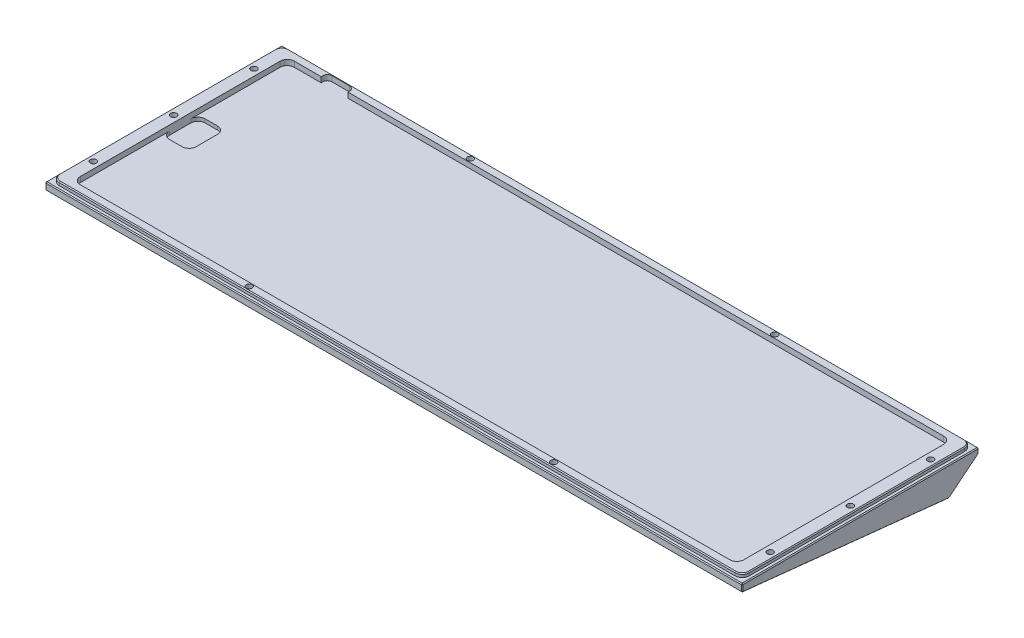
SolidWorks part; units mm, degrees
material "6061-T6 (SS)"
ref_plane "Front Plane" through (0, 0, 0) normal (0, 0, 1) x (1, 0, 0)
ref_plane "Top Plane" through (0, 0, 0) normal (0, 1, 0) x (1, 0, 0)
ref_plane "Right Plane" through (0, 0, 0) normal (1, 0, 0) x (0, 0, -1)
sketch "Sketch1" plane through (0, 0, 0) normal (0, 1, 0) x (1, 0, 0)
  line L1 (0, 0) -> (390.7, 0)
  line L2 (0, 0) -> (0, 132.7)
  line L3 (0, 132.7) -> (390.7, 132.7)
  line L4 (390.7, 0) -> (390.7, 132.7)
  dimension "D1" = 390.7
  dimension "D2" = 132.7
extrude "MainBody" add sketch "Sketch1" along normal blind 18.5
sketch "Sketch2" plane through (0, 18.5, 0) normal (0, 1, 0) x (1, 0, 0)
  line L0 (390.7, 132.7) -> (0, 132.7) construction
  line L1 (2, 130.7) -> (388.7, 130.7)
  line L2 (2, 130.7) -> (2, 2)
  line L3 (2, 2) -> (388.7, 2)
  line L4 (388.7, 130.7) -> (388.7, 2)
  line L5 (0, 132.7) -> (0, 0) construction
  line L7 (0, 132.7) -> (390.7, 132.7)
  line L8 (0, 132.7) -> (0, 0)
  line L9 (0, 0) -> (390.7, 0)
  line L10 (390.7, 132.7) -> (390.7, 0)
  point P4 (195.35, 130.7)
  point P7 (195.35, 132.7)
  point P8 (2, 66.35)
  point P11 (0, 66.35)
  line M5 (0, 132.7) -> (0, 0)
  line M6 (0, 0) -> (390.7, 0)
  line M7 (390.7, 0) -> (390.7, 132.7)
  line M8 (390.7, 132.7) -> (0, 132.7)
  dimension "D1" = 2
  dimension "D2" = 2
extrude "AligmentLip" cut sketch "Sketch2" against normal blind 2 contours L1 L4 L3 L2 M8 M5 M6 M7
sketch "Sketch3" plane through (0, 0, 0) normal (-1, 0, 0) x (0, 0, 1)
  line L0 (-132.7, 13.5) -> (-116.0289, 0)
  line L1 (-132.7, 16.5) -> (-132.7, 0) construction
  line L2 (-132.7, 0) -> (0, 0) construction
  line L3 (-116.0289, 0) -> (0, 12.1951)
  line L4 (0, 16.5) -> (0, 0) construction
  line L5 (-132.7, 16.5) -> (0, 16.5) construction
  line L7 (-132.7, 16.5) -> (0, 16.5)
  line L8 (-132.7, 16.5) -> (-132.7, 0)
  line L9 (-132.7, 0) -> (0, 0)
  line L10 (0, 16.5) -> (0, 0)
  line M4 (-132.7, 16.5) -> (-132.7, 0)
  line M5 (-132.7, 0) -> (0, 0)
  line M6 (0, 0) -> (0, 16.5)
  dimension "D1" = 6
  dimension "D2" = 135
  dimension "D3" = 3
extrude "TypingAngle" cut sketch "Sketch3" against normal through all contours L0 M4 M5 | L3 M5 M6
sketch "Sketch4" plane through (0, 18.5, 0) normal (0, 1, 0) x (1, 0, 0)
  line L0 (2, 130.7) -> (388.7, 130.7) construction
  line L1 (9.35, 126.35) -> (381.35, 126.35)
  line L2 (9.35, 126.35) -> (9.35, 6.35)
  line L3 (9.35, 6.35) -> (381.35, 6.35)
  line L4 (381.35, 126.35) -> (381.35, 6.35)
  line L5 (2, 130.7) -> (2, 2) construction
  point P4 (195.35, 126.35)
  point P7 (195.35, 130.7)
  point P8 (9.35, 66.35)
  point P11 (2, 66.35)
  dimension "D1" = 372
  dimension "D2" = 120
extrude "PCBCutout" cut sketch "Sketch4" against normal blind 3
sketch "Sketch8" plane through (0, 18.5, 0) normal (0, 1, 0) x (1, 0, 0)
  line L0 (195.35, 132.7) -> (195.35, 0) construction
  line L1 (390.7, 132.7) -> (0, 132.7) construction
  line L2 (0, 0) -> (390.7, 0) construction
  line L3 (0, 66.35) -> (195.35, 66.35) construction
  line L4 (0, 132.7) -> (0, 0) construction
  line L5 (2, 130.7) -> (388.7, 130.7) construction
  line L6 (2, 2) -> (388.7, 2) construction
  line L7 (2, 130.7) -> (2, 2) construction
  point P11 (110, 128.3)
  point P12 (5.7, 111.35)
  point P13 (5.7, 66.35)
  point P14 (5.7, 21.35)
  point P16 (110, 4.4)
  point P17 (0, 0)
  point P18 (0, 0)
  point P27 (280.7, 4.4)
  point P28 (385, 21.35)
  point P29 (385, 66.35)
  point P30 (385, 111.35)
  point P31 (280.7, 128.3)
  dimension "D1" = 2.4
  dimension "D2" = 2.4
  dimension "D3" = 110
  dimension "D4" = 45
  dimension "D5" = 45
  dimension "D6" = 3.7
hole_wizard "M3 Clearance Hole1" positions "3DSketch7" profile "Sketch10" hole size "M3" standard "ANSI Metric" end condition through all
sketch3d "3DSketch7"
  point P0 (110, 18.5, -128.3)
  point P3 (5.7, 18.5, -111.35)
  point P6 (5.7, 18.5, -66.35)
  point P9 (5.7, 18.5, -21.35)
  point P12 (110, 18.5, -4.4)
  point P15 (280.7, 18.5, -128.3)
  point P18 (280.7, 18.5, -4.4)
  point P21 (385, 18.5, -21.35)
  point P24 (385, 18.5, -66.35)
  point P27 (385, 18.5, -111.35)
sketch "Sketch10" plane through (110, 18.5, -128.3) normal (1, 0, 0) x (0, 0, 1)
  line L0 (0, 0) -> (0, 18.5)
  line L1 (0, 18.5) -> (1.7, 18.5)
  line L2 (1.7, 18.5) -> (1.7, 0)
  line L5 (1.7, 0) -> (0, 0)
  line L11 (0, -6.35) -> (0, 107.95) construction
  dimension "Thru Hole Dia." = 3.4
  dimension "Thru Hole Depth" = 18.5
sketch "Sketch11" plane through (0, 15.5, 0) normal (0, 1, 0) x (1, 0, 0)
  line L0 (195.35, 132.7) -> (195.35, 0) construction
  line L1 (0, 0) -> (390.7, 0) construction
  circle A0 centre (110, 128.3) radius 3.25
  circle A1 centre (5.7, 111.35) radius 3.25
  circle A2 centre (5.7, 66.35) radius 3.25
  circle A3 centre (5.7, 21.35) radius 3.25
  circle A4 centre (110, 4.4) radius 3.25
  circle A5 centre (280.7, 4.4) radius 3.25
  circle A6 centre (385, 21.35) radius 3.25
  circle A7 centre (385, 66.35) radius 3.25
  circle A8 centre (385, 111.35) radius 3.25
  circle A9 centre (280.7, 128.3) radius 3.25
  dimension "D1" = 6.5
extrude "Cut-Extrude2" cut sketch "Sketch11" against normal through all from offset 1 offset against normal yes
sketch "Sketch12" plane through (0, 18.5, 0) normal (0, 1, 0) x (1, 0, 0)
  line L0 (381.35, 126.35) -> (9.35, 126.35) construction
  line L1 (28.4, 126.35) -> (43.4, 126.35)
  line L2 (28.4, 126.35) -> (28.4, 129.85)
  line L3 (28.4, 129.85) -> (43.4, 129.85)
  line L4 (43.4, 126.35) -> (43.4, 129.85)
  line L5 (0, 132.7) -> (0, 0) construction
  point P6 (35.9, 129.85)
  dimension "D1" = 15
  dimension "D2" = 3.5
  dimension "D3" = 35.9
extrude "Cut-Extrude3" cut sketch "Sketch12" against normal up to surface (3 mm away) up to face at (195.35, 15.5, -66.35)
fillet "Fillet1" radius 2.5 2 edges at (43.4, 17, -129.85) (28.4, 17, -129.85)
sketch "Sketch13" plane through (0, 15.5, 0) normal (0, 1, 0) x (1, 0, 0)
  line L0 (9.35, 126.35) -> (9.35, 6.35) construction
  line L1 (9.35, 76.35) -> (24.35, 76.35)
  line L2 (9.35, 76.35) -> (9.35, 56.35)
  line L3 (9.35, 56.35) -> (24.35, 56.35)
  line L4 (24.35, 76.35) -> (24.35, 56.35)
  line L5 (2, 130.7) -> (2, 2) construction
  point P6 (9.35, 66.35)
  point P9 (2, 66.35)
  dimension "D1" = 15
  dimension "D2" = 20
extrude "Cut-Extrude4" cut sketch "Sketch13" against normal blind 2
fillet "Fillet2" radius 4 12 edges at (381.35, 17, -126.35) (388.7, 17.5, -130.7) (388.7, 17.5, -2) (381.35, 17, -6.35) (9.35, 17, -6.35) (2, 17.5, -2) (9.35, 17, -126.35) (2, 17.5, -130.7) (9.35, 14.5, -56.35) (24.35, 14.5, -56.35) (9.35, 14.5, -76.35) (24.35, 14.5, -76.35)
chamfer "Chamfer1" distance 0.5 angle 45 13 edges at (195.35, 12.1951, 0) (390.7, 15, -132.7) (0, 15, -132.7) (0, 6.75, -124.3644) (390.7, 6.75, -124.3644) (390.7, 6.0976, -58.0144) (390.7, 14.3476, 0) (0, 6.0976, -58.0144) (0, 14.3476, 0) (0, 16.5, -66.35) (195.35, 16.5, 0) (390.7, 16.5, -66.35) (195.35, 16.5, -132.7)
chamfer "Chamfer2" distance 0.5 angle 45 8 edges at (388.7, 18.5, -66.35) (387.5284, 18.5, -129.5284) (387.5284, 18.5, -3.1716) (195.35, 18.5, -130.7) (195.35, 18.5, -2) (3.1716, 18.5, -129.5284) (3.1716, 18.5, -3.1716) (2, 18.5, -66.35)
sketch "Sketch17" plane through (0, 12.0619, -1.2678) normal (0, -0.9945, 0.1045) x (1, 0, 0)
  line L0 (198.1, -60.7253) -> (196.1, -60.7253) construction
  line L1 (198.1, -68.7253) -> (196.1, -68.7253)
  line L2 (198.1, -68.7253) -> (198.1, -52.7253)
  line L3 (198.1, -52.7253) -> (196.1, -52.7253)
  line L4 (196.1, -68.7253) -> (196.1, -52.7253)
  line L5 (202.6, -61.2253) -> (200.6, -61.2253)
  line L6 (202.6, -61.2253) -> (202.6, -48.7253)
  line L7 (202.6, -48.7253) -> (200.6, -48.7253)
  line L8 (200.6, -61.2253) -> (200.6, -48.7253)
  line L9 (193.6, -61.2253) -> (191.6, -61.2253)
  line L10 (193.6, -61.2253) -> (193.6, -53.2253)
  line L11 (193.6, -53.2253) -> (191.6, -53.2253)
  line L12 (191.6, -61.2253) -> (191.6, -53.2253)
  line L13 (190.1, -61.2253) -> (188.1, -61.2253)
  line L14 (190.1, -61.2253) -> (190.1, -53.2253)
  line L15 (190.1, -53.2253) -> (188.1, -53.2253)
  line L16 (188.1, -61.2253) -> (188.1, -53.2253)
  line L17 (186.6, -61.2253) -> (184.6, -61.2253)
  line L18 (186.6, -61.2253) -> (186.6, -53.2253)
  line L19 (186.6, -53.2253) -> (184.6, -53.2253)
  line L20 (184.6, -61.2253) -> (184.6, -53.2253)
  line L25 (202.6, -61.2253) -> (188.1, -61.2253) construction
  line L26 (390.2, -115.3933) -> (0.5, -115.3933) construction
  line L27 (194.1, -64.7253) -> (198.1, -64.7253)
  line L28 (194.1, -62.7253) -> (198.1, -62.7253)
  line L29 (390.7, 1.2747) -> (0, 1.2747) construction
  line L31 (206.1, -53.2253) -> (204.1, -53.2253)
  line L32 (206.1, -53.2253) -> (206.1, -48.7253)
  line L33 (206.1, -48.7253) -> (204.1, -48.7253)
  line L34 (204.1, -53.2253) -> (204.1, -48.7253)
  circle A0 centre (201.6, -63.7253) radius 1
  circle A2 centre (194.1, -63.7253) radius 1
  circle A3 centre (197.1, -67.7253) radius 1
  circle A4 centre (197.1, -53.7253) radius 1
  circle A5 centre (201.6, -60.2253) radius 1
  circle A6 centre (201.6, -49.7253) radius 1
  circle A7 centre (205.1, -52.2253) radius 1
  circle A8 centre (205.1, -49.7253) radius 1
  circle A9 centre (192.6, -60.2253) radius 1
  circle A10 centre (192.6, -54.2253) radius 1
  circle A11 centre (189.1, -60.2253) radius 1
  circle A12 centre (189.1, -54.2253) radius 1
  circle A13 centre (185.6, -60.2253) radius 1
  circle A14 centre (185.6, -54.2253) radius 1
  point P28 (195.35, -61.2253)
  point P29 (201.6, -61.2253)
  point P33 (195.35, -115.3933)
  point P44 (197.1, -68.7253)
  dimension "D12" = 2
  dimension "D13" = 12.5
  dimension "D16" = 2
  dimension "D1" = 16
  dimension "D2" = 2
  dimension "D3" = 0
  dimension "D4" = 2.5
  dimension "D5" = 2.5
  dimension "D6" = 1.5
  dimension "D7" = 1.5
  dimension "D8" = 8
  dimension "D9" = 0.5
  dimension "D10" = 1.5
  dimension "D11" = 2.5
  dimension "D14" = 4.5
  dimension "D15" = 50
  dimension "D17" = 2
  dimension "D18" = 3
  dimension "D19" = 11
extrude "Cut-Extrude5" cut sketch "Sketch17" against normal blind 1 contours A7 | A8 L34 A7 L32 | A8 | A6 | A6 L8 A5 L6 | A5 | A4 | A4 L4 L28 L2 | L28 L4 L27 L2 | A3 L2 L27 L4 | A3 | A2 L27 L4 L28 | A2 | A0 | A9 | A10 L12 A9 L10 | A10 | A12 L16 A11 L14 | A11 | A12 | A14 | A14 L20 A13 L18 | A13
